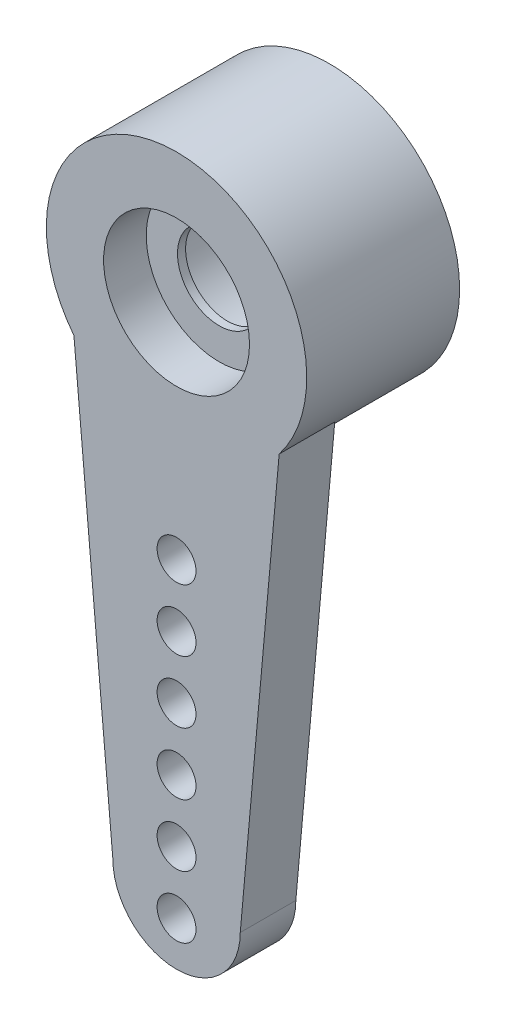
SolidWorks part; units mm, degrees
material "Nylon 6/10"
ref_plane "Front Plane" through (0, 0, 0) normal (0, 0, 1) x (1, 0, 0)
ref_plane "Top Plane" through (0, 0, 0) normal (0, 1, 0) x (1, 0, 0)
ref_plane "Right Plane" through (0, 0, 0) normal (1, 0, 0) x (0, 0, -1)
ref_plane "Plane1" through (0, 0, -7.033) normal (0, 0, 1) x (1, 0, 0)
sketch "Sketch1" plane through (0, 0, -7.033) normal (0, 0, 1) x (1, 0, 0)
  circle A0 centre (-5.5, 0) radius 3.5687
  circle A1 centre (-5.5, 0) radius 2
  dimension "D1" = 7.1374
extrude "Boss-Extrude1" add sketch "Sketch1" along normal blind 4.191
sketch "Sketch5" plane through (0, 0, -4.233) normal (0, 0, 1) x (1, 0, 0)
  circle A0 centre (-5.5, 0) radius 1.143
  circle A1 centre (-5.5, 0) radius 2 construction
  circle A2 centre (-5.5, 0) radius 2
  dimension "D1" = 2.286
extrude "Boss-Extrude2" add sketch "Sketch5" along normal offset from surface (0.2226 mm away) 1.1684 up to face at (-1.9313, 0, -2.842)
sketch "Sketch6" plane through (0, 0, -2.842) normal (0, 0, 1) x (1, 0, 0)
  line L0 (-3.7537, -14.0907) -> (-2.6869, -2.196)
  line L1 (-7.2462, -14.0907) -> (-8.313, -2.196)
  line L2 (-5.5, 0) -> (-5.5, -14.0907) construction
  line L3 (-5.5, -14.6241) -> (-5.5, -12.9223) construction
  arc A0 (-7.2462, -14.0907) -> (-3.7537, -14.0907) centre (-5.5, -14.0907) ccw
  circle A1 centre (-5.5, 0) radius 3.5687 construction
  circle A2 centre (-5.5, 0) radius 3.5687 construction
  circle A3 centre (-5.5, -12.9223) radius 0.5334
  circle A4 centre (-5.5, -14.6241) radius 0.5334
  circle A5 centre (-5.5, -11.2205) radius 0.5334
  circle A6 centre (-5.5, -9.5186) radius 0.5334
  circle A7 centre (-5.5, -7.8169) radius 0.5334
  circle A8 centre (-5.5, -6.1151) radius 0.5334
  arc A9 (-2.6869, -2.196) -> (-8.313, -2.196) centre (-5.5, 0) cw
  dimension "D1" = 3.4925
  dimension "D2" = 15.8369
  dimension "D4" = 1.0668
  dimension "D3" = 5.6261
  dimension "D6" = 1.7018
  dimension "D5" = 6
extrude "Boss-Extrude3" add sketch "Sketch6" against normal blind 1.524
scale "Scale1" bodies to scale 103 scale about centroid uniform scaling yes scale factor 0.1
